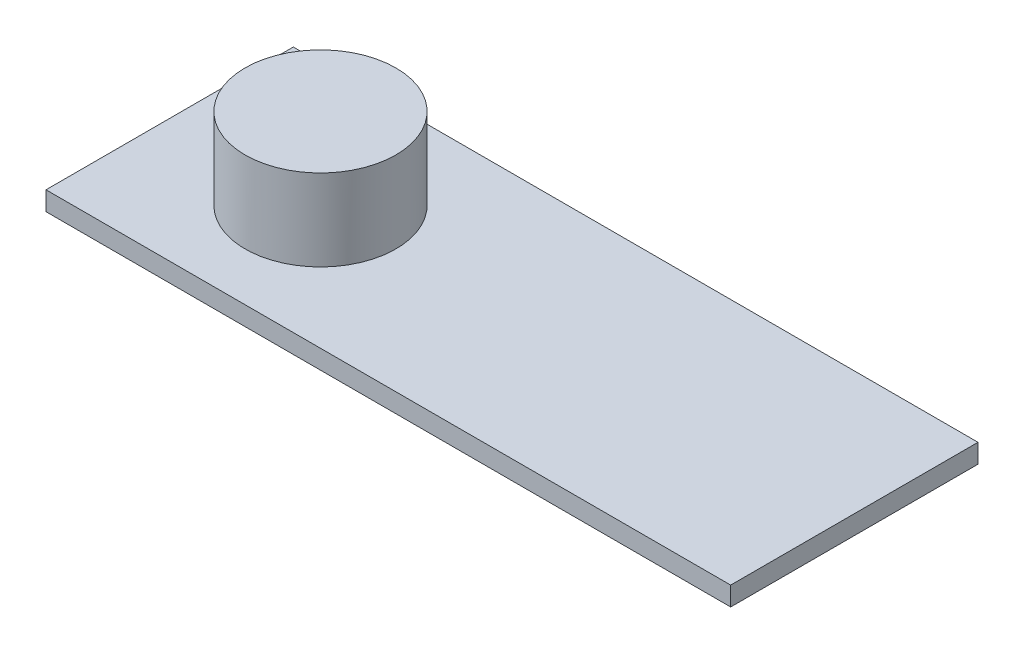
SolidWorks part; units mm, degrees
ref_plane "Front Plane" through (0, 0, 0) normal (0, 0, 1) x (1, 0, 0)
ref_plane "Top Plane" through (0, 0, 0) normal (0, 1, 0) x (1, 0, 0)
ref_plane "Right Plane" through (0, 0, 0) normal (1, 0, 0) x (0, 0, -1)
sketch "Sketch1" plane through (0, 0, 0) normal (0, 1, 0) x (1, 0, 0)
  line L1 (-28.829, -10.414) -> (28.829, -10.414)
  line L2 (-28.829, -10.414) -> (-28.829, 10.414)
  line L3 (-28.829, 10.414) -> (28.829, 10.414)
  line L4 (28.829, -10.414) -> (28.829, 10.414)
  line L5 (-28.829, -10.414) -> (28.829, 10.414) construction
  line L6 (-28.829, 10.414) -> (28.829, -10.414) construction
  point P0 (0, 0)
  dimension "D1" = 57.658
  dimension ".83" = 20.828
extrude "Boss-Extrude1" add sketch "Sketch1" along normal blind 1.6
sketch "Sketch2" plane through (0, 1.6, 0) normal (0, 1, 0) x (1, 0, 0)
  line L0 (-28.829, 10.414) -> (-28.829, -10.414) construction
  circle A0 centre (-16.129, 0) radius 6.35
  point P4 (0, 0)
  dimension "D1" = 12.7
  dimension "D2" = 12.7
extrude "Boss-Extrude2" add sketch "Sketch2" along normal blind 6.858
